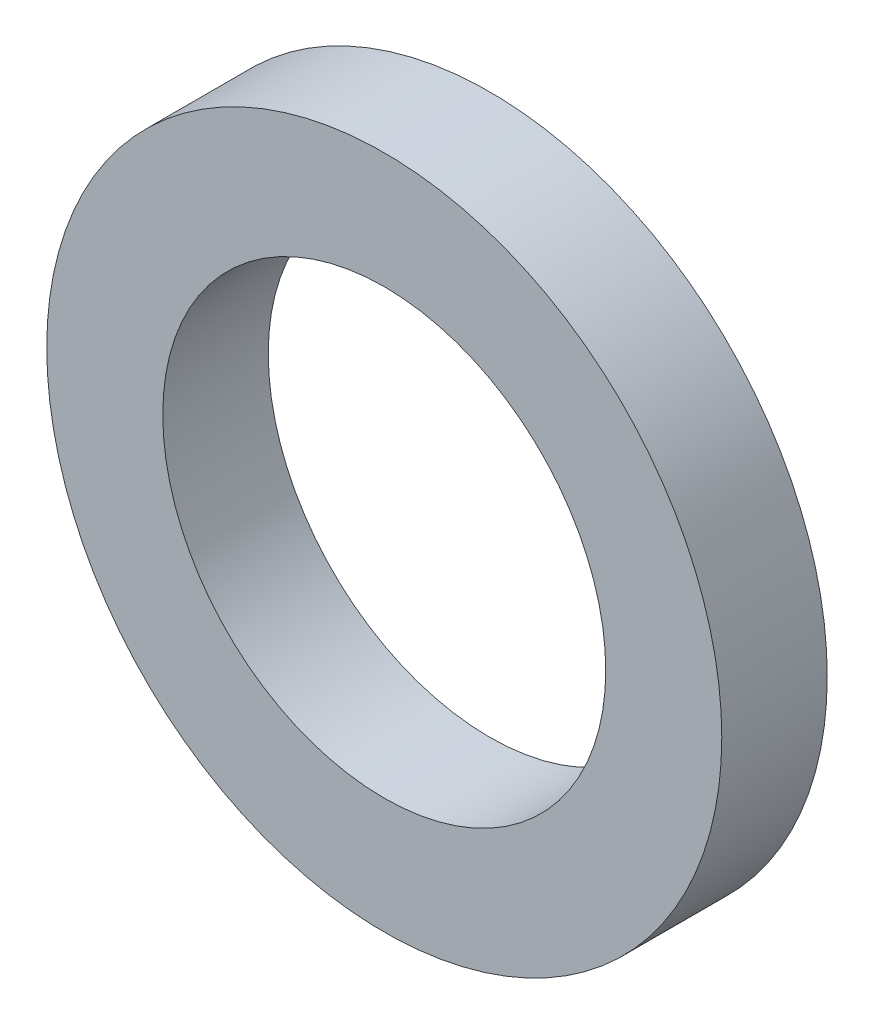
SolidWorks part; units mm, degrees
ref_plane "前基準面" through (0, 0, 0) normal (0, 0, 1) x (1, 0, 0)
ref_plane "上基準面" through (0, 0, 0) normal (0, 1, 0) x (1, 0, 0)
ref_plane "右基準面" through (0, 0, 0) normal (1, 0, 0) x (0, 0, -1)
sketch "草圖1" plane through (0, 0, 0) normal (0, 0, 1) x (1, 0, 0)
  circle A0 centre (0, 0) radius 3.2
  circle A1 centre (0, 0) radius 2.1
  dimension "D1" = 6.4
  dimension "D2" = 4.2
extrude "填料-伸長1" add sketch "草圖1" along normal blind 1
